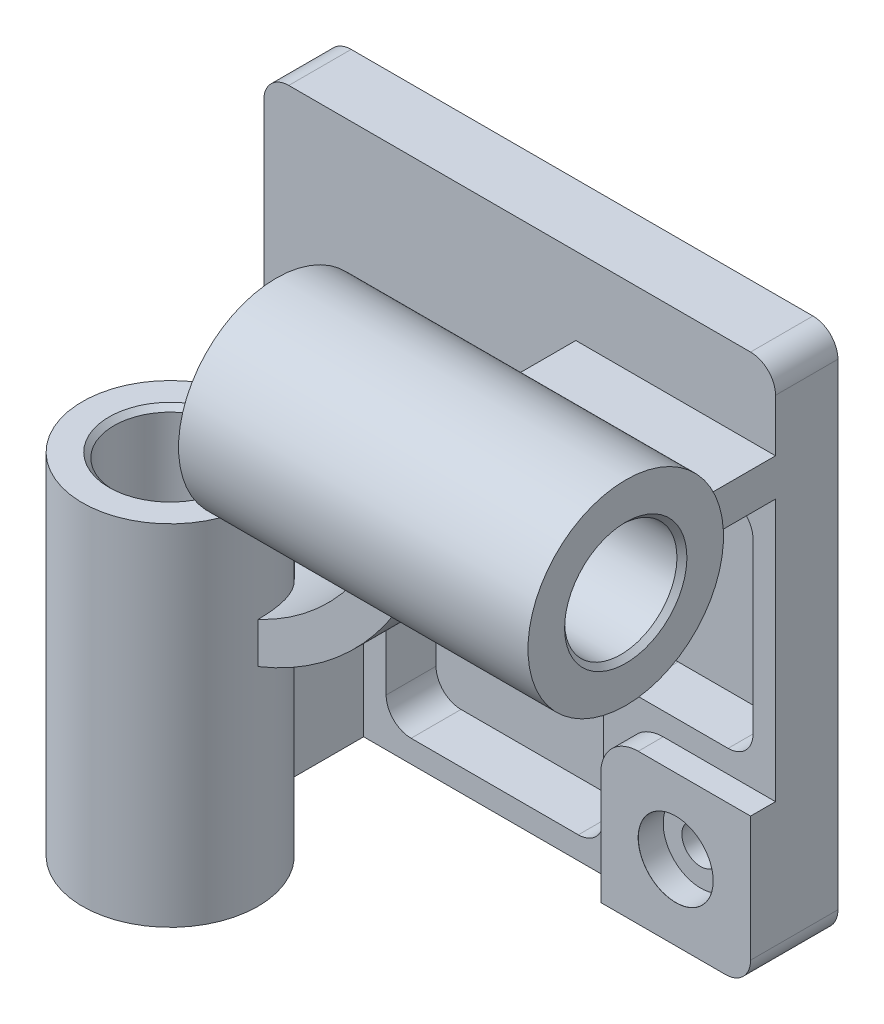
SolidWorks part; units mm, degrees
material "Cast Alloy Steel"
ref_plane "Front Plane" through (0, 0, 0) normal (0, 0, 1) x (1, 0, 0)
ref_plane "Top Plane" through (0, 0, 0) normal (0, 1, 0) x (1, 0, 0)
ref_plane "Right Plane" through (0, 0, 0) normal (1, 0, 0) x (0, 0, -1)
sketch "Sketch1" plane through (0, 0, 0) normal (0, 0, 1) x (1, 0, 0)
  line L1 (-25, 31) -> (180, 31)
  line L2 (-25, 31) -> (-25, -180)
  line L3 (-25, -180) -> (180, -180)
  line L4 (180, 31) -> (180, -180)
  dimension "D1" = 211
  dimension "D2" = 205
  dimension "D3" = 180
  dimension "D4" = 180
extrude "Boss-Extrude1" add sketch "Sketch1" along normal blind 25
sketch "Sketch2" plane through (0, 0, 0) normal (0, 0, -1) x (-1, 0, 0)
  line L1 (-180, -180) -> (-120, -180)
  line L2 (-180, -180) -> (-180, -120)
  line L3 (-180, -120) -> (-120, -120)
  line L4 (-120, -180) -> (-120, -120)
  dimension "D1" = 60
  dimension "D2" = 60
extrude "Boss-Extrude2" add sketch "Sketch2" against normal blind 10 from surface at -25 starting at face at (77.5, -74.5, 25)
fillet "Fillet1" radius 10 4 edges at (-25, -180, 12.5) (-25, 31, 12.5) (180, 31, 12.5) (180, -180, 17.5)
sketch "Sketch4" plane through (0, 0, 0) normal (0, 0, 1) x (1, 0, 0)
  line L0 (0, 51.84) -> (0, -180) construction
  line L1 (-15, -180) -> (120, -180) construction
  line L2 (0, -180) -> (0, -205.4092) construction
  line L3 (-40.958, 0) -> (0, 0) construction
  line L4 (0, 0) -> (205.5534, 0) construction
  line L5 (0, -180) -> (0, -100)
  line L7 (15, -114.0175) -> (15, -180)
  line L8 (15, -180) -> (0, -180)
  line L9 (180, 0) -> (100, 0)
  line L10 (180, -120) -> (180, 21) construction
  line L12 (114.0175, -15) -> (180, -15)
  line L13 (180, -15) -> (180, 0)
  arc A0 (100, 0) -> (0, -100) centre (0, 0) cw
  arc A1 (15, -114.0175) -> (114.0175, -15) centre (0, 0) ccw
  point P8 (15, -147.0088)
  dimension "D5" = 15
  dimension "D1" = 80
  dimension "D2" = 15
  dimension "D3" = 80
  dimension "D4" = 15
extrude "Boss-Extrude3" add sketch "Sketch4" along normal blind 95
sketch "Sketch5" plane through (0, -180, 0) normal (0, -1, 0) x (1, 0, 0)
  line L0 (7.5, 95) -> (7.5, 0) construction
  line L1 (15, 95) -> (0, 95) construction
  line L2 (-15, 0) -> (170, 0) construction
  line L3 (7.5, 0) -> (7.5, -18.3844) construction
  circle A0 centre (7.5, 95) radius 35.1667
  circle A1 centre (7.5, 95) radius 22.5
  dimension "D1" = 70.3333
  dimension "D3" = 45
  dimension "D2" = 95
extrude "Boss-Extrude4" add sketch "Sketch5" against normal blind 140 from offset 10 contours A0
sketch "Sketch6" plane through (0, -190, 0) normal (0, -1, 0) x (1, 0, 0)
  line L0 (7.5, 130.1667) -> (7.5, 0) construction
  line L1 (-15, 0) -> (170, 0) construction
  line L2 (-27.6667, 95) -> (7.5, 95) construction
  line L3 (7.5, 95) -> (42.6667, 95) construction
  circle A0 centre (7.5, 95) radius 35.1667 construction
  arc A1 (15, 60.6424) -> (42.6667, 95) centre (7.5, 95) ccw construction
  circle A2 centre (7.5, 95) radius 22.5
  dimension "D1" = 45
extrude "Cut-Extrude1" cut sketch "Sketch6" against normal blind 140
sketch "Sketch7" plane through (180, 0, 0) normal (1, 0, 0) x (0, 0, -1)
  line L0 (-95, -7.5) -> (0, -7.5) construction
  line L1 (0, -170) -> (0, 21) construction
  circle A0 centre (-95, -7.5) radius 39.165
  dimension "D1" = 78.33
  dimension "D2" = 95
extrude "Boss-Extrude5" add sketch "Sketch7" against normal blind 140 from offset 10
sketch "Sketch8" plane through (190, 0, 0) normal (1, 0, 0) x (0, 0, -1)
  line L0 (-134.165, -7.5) -> (-95, -7.5) construction
  line L1 (-95, -7.5) -> (0, -7.5) construction
  line L2 (0, -170) -> (0, 21) construction
  circle A0 centre (-95, -7.5) radius 39.165 construction
  circle A1 centre (-95, -7.5) radius 22.5
  dimension "D1" = 45
extrude "Cut-Extrude2" cut sketch "Sketch8" against normal through all
sketch "Sketch10" plane through (0, 0, 25) normal (0, 0, 1) x (1, 0, 0)
  line L1 (171, -33.4288) -> (171, -101)
  line L2 (161, -111) -> (121, -111)
  line L3 (111, -121) -> (111, -161)
  line L4 (101, -171) -> (34, -171)
  line L6 (180, -15) -> (114.0175, -15) construction
  line L7 (180, -120) -> (120, -120) construction
  line L8 (180, -120) -> (180, -15) construction
  line L9 (15, -180) -> (120, -180) construction
  line L10 (120, -120) -> (120, -180) construction
  line L11 (15, -114.0175) -> (15, -180) construction
  line L12 (24, -161) -> (24, -136.5278)
  line L14 (24, -136.5278) -> (24, -121.6553)
  line L15 (164.3313, -24) -> (132.5032, -24)
  line L16 (132.5032, -24) -> (121.6553, -24)
  arc A3 (164.3313, -24) -> (171, -33.4288) centre (161, -33.4288) cw
  arc A4 (171, -101) -> (161, -111) centre (161, -101) cw
  arc A5 (121, -111) -> (111, -121) centre (121, -121) ccw
  arc A6 (111, -161) -> (101, -171) centre (101, -161) cw
  arc A7 (24, -161) -> (34, -171) centre (34, -161) ccw
  arc A15 (24, -121.6553) -> (121.6553, -24) centre (0, 0) ccw
  arc A16 (15, -114.0175) -> (114.0175, -15) centre (0, 0) ccw construction
  point P20 (24, -136.5278)
  dimension "D1" = 9
  dimension "D6" = 9
  dimension "D7" = 10
  dimension "D8" = 9
  dimension "D2" = 9
  dimension "D3" = 9
  dimension "D4" = 9
  dimension "D5" = 9
extrude "Cut-Extrude5" cut sketch "Sketch10" along normal blind 35 and the other way blind 15 from offset 5 offset against normal yes
sketch "Sketch13" plane through (0, 0, 35) normal (0, 0, 1) x (1, 0, 0)
  line L0 (150, -120) -> (150, -180) construction
  line L1 (180, -120) -> (120, -120) construction
  line L2 (120, -180) -> (170, -180) construction
  line L3 (120, -150) -> (180, -150) construction
  line L4 (120, -120) -> (120, -180) construction
  line L5 (180, -170) -> (180, -120) construction
  point P15 (150, -150)
hole_wizard "CBORE for M8 Hex Head Bolt2" positions "Sketch13" profile "Sketch15" counterbore size "M8" standard "ANSI Metric" end condition through all
sketch "Sketch15" plane through (150, -150, 35) normal (1, 0, 0) x (0, -1, 0)
  line L0 (0, 0) -> (0, 35)
  line L1 (0, 35) -> (7.5, 35)
  line L3 (7.5, 35) -> (7.5, 10)
  line L4 (15, 10) -> (7.5, 10)
  line L5 (15, 10) -> (15, 0.025)
  line L6 (15, 0.025) -> (15.025, 0)
  line L7 (15.025, 0) -> (0, 0)
  line L8 (-15, 0.025) -> (-15.025, 0) construction
  line L11 (0, -6.35) -> (0, 107.95) construction
  dimension "Thru Hole Dia." = 15
  dimension "Thru Hole Depth" = 35
  dimension "C'Bore Dia." = 30
  dimension "C'Bore Depth" = 10
  dimension "Near C'Sink Dia." = 30.05
  dimension "Near C'Sink Angle" = 90
fillet "Fillet2" radius 15 1 edges at (120, -120, 30)
fillet "Fillet3" radius 10 2 edges at (121.6553, -24, 15) (24, -121.6553, 15)
chamfer "Chamfer1" distance 2 angle 45 2 edges at (30, -190, 95) (30, -50, 95)
chamfer "Chamfer2" distance 2 angle 45 2 edges at (50, 15, 95) (190, 15, 95)
equation "\"A\"=211"
equation "\"D1@Sketch1\"=\"A\""
equation "\"B\"=205"
equation "\"D2@Sketch1\"=\"B\""
equation "\"C\"=180"
equation "\"D3@Sketch1\"=\"C\""
equation "\"X\"= \"A\" / 3mm"
equation "\"D1@Sketch5\"=\"X\""
equation "\"E\"=45"
equation "\"D3@Sketch5\"=\"E\""
equation "\"D\"= 140mm"
equation "\"Y\"= \"B\" / 3mm + 10mm"
